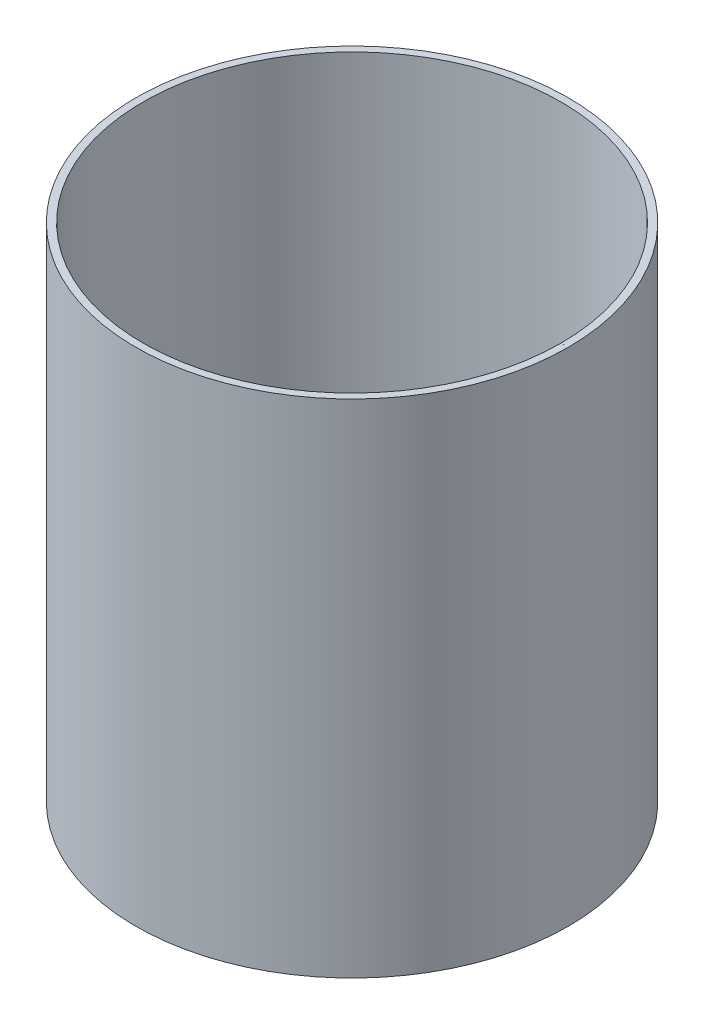
SolidWorks part; units mm, degrees
ref_plane "Front Plane" through (0, 0, 0) normal (0, 0, 1) x (1, 0, 0)
ref_plane "Top Plane" through (0, 0, 0) normal (0, 1, 0) x (1, 0, 0)
ref_plane "Right Plane" through (0, 0, 0) normal (1, 0, 0) x (0, 0, -1)
sketch "Sketch1" plane through (0, 0, 0) normal (0, 0, 1) x (1, 0, 0)
  line L0 (0, 0) -> (0, 691.9014) construction
  line L2 (750, 900) -> (776, 900)
  line L3 (750, 900) -> (750, -900)
  line L4 (750, -900) -> (776, -900)
  line L5 (776, 900) -> (776, -900)
  line L6 (750, 900) -> (776, -900) construction
  line L7 (750, -900) -> (776, 900) construction
  point P3 (763, 0)
  point P8 (0, 0)
  dimension "D1" = 750
  dimension "D2" = 26
  dimension "D3" = 1800
revolve "Revolve1" add sketch "Sketch1" angle 359.99 about L0
